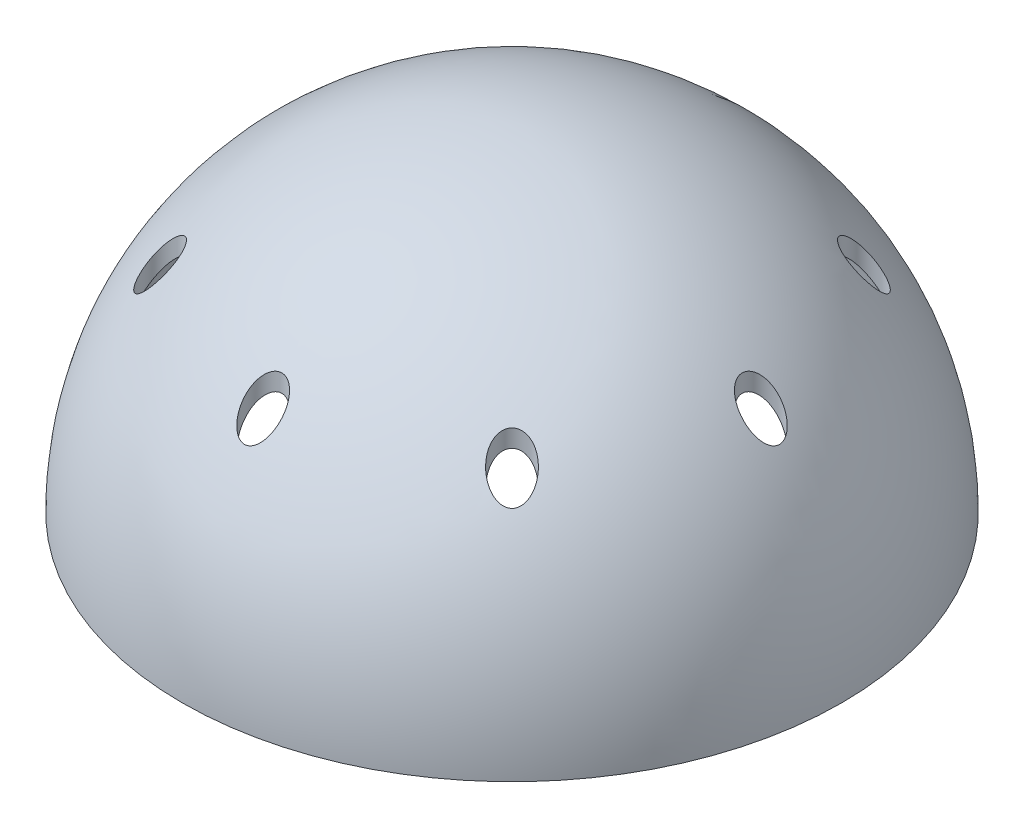
SolidWorks part; units mm, degrees
ref_plane "Front Plane" through (0, 0, 0) normal (0, 0, 1) x (1, 0, 0)
ref_plane "Top Plane" through (0, 0, 0) normal (0, 1, 0) x (1, 0, 0)
ref_plane "Right Plane" through (0, 0, 0) normal (1, 0, 0) x (0, 0, -1)
sketch "Sketch1" plane through (0, 0, 0) normal (0, 1, 0) x (1, 0, 0)
  line L0 (-26.5, 0) -> (-25.5, 0)
  line L1 (25.5, 0) -> (26.5, 0)
  line L2 (-25.5, 0) -> (25.5, 0) construction
  arc A0 (25.5, 0) -> (-25.5, 0) centre (0, 0) ccw
  arc A1 (26.5, 0) -> (-26.5, 0) centre (0, 0) ccw
  dimension "D1" = 51
  dimension "D2" = 53
revolve "Revolve1" add sketch "Sketch1" angle 180 about L2
sketch "Sketch2" plane through (0, 0, 0) normal (0, -1, 0) x (1, 0, 0)
  line L0 (0, 0) -> (0, 20) construction
  circle A0 centre (0, 20) radius 1.5
  circle A1 centre (14.1421, 14.1421) radius 1.5
  circle A2 centre (20, 0) radius 1.5
  circle A3 centre (14.1421, -14.1421) radius 1.5
  circle A4 centre (0, -20) radius 1.5
  circle A5 centre (-14.1421, -14.1421) radius 1.5
  circle A6 centre (-20, 0) radius 1.5
  circle A7 centre (-14.1421, 14.1421) radius 1.5
  dimension "D2" = 3
  dimension "D1" = 20
  dimension "D3" = 8
extrude "Cut-Extrude1" cut sketch "Sketch2" against normal blind 32
